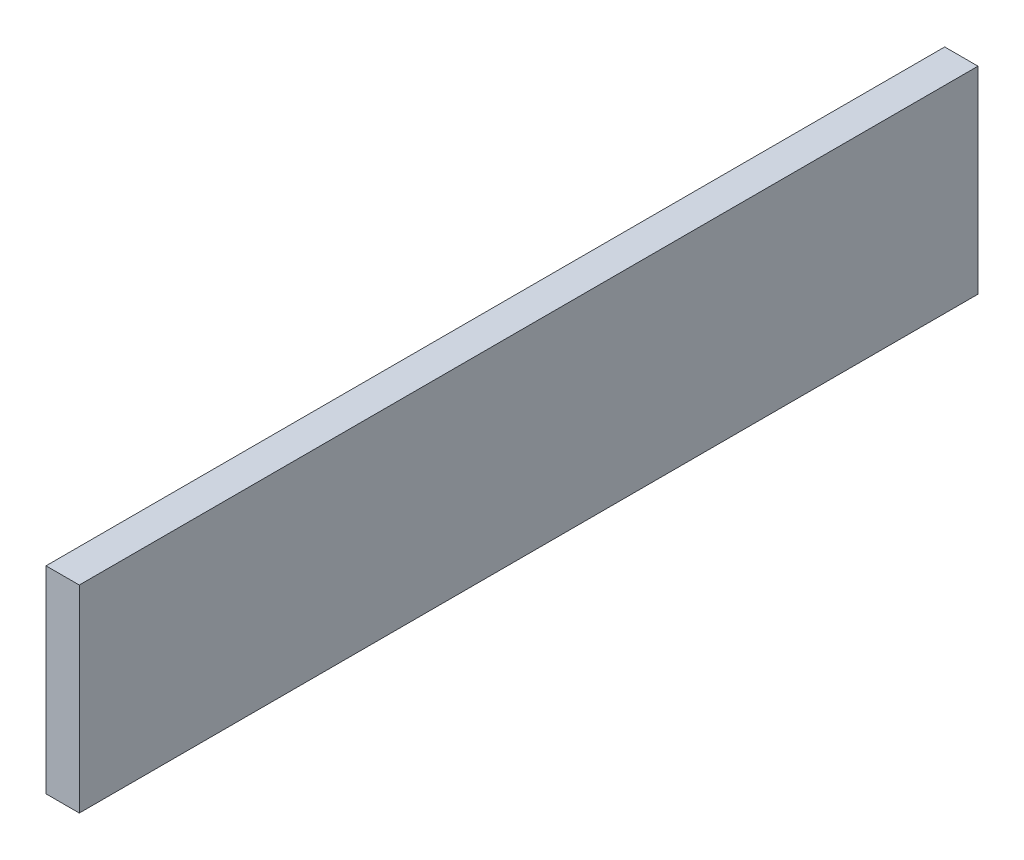
SolidWorks part; units mm, degrees
ref_plane "Alzado" through (0, 0, 0) normal (0, 0, 1) x (1, 0, 0)
ref_plane "Planta" through (0, 0, 0) normal (0, 1, 0) x (1, 0, 0)
ref_plane "Vista lateral" through (0, 0, 0) normal (1, 0, 0) x (0, 0, -1)
sketch "Croquis1" plane through (0, 0, 0) normal (1, 0, 0) x (0, 0, -1)
  line L1 (0, 0) -> (405, 0)
  line L2 (0, 0) -> (0, 89)
  line L3 (0, 89) -> (405, 89)
  line L4 (405, 0) -> (405, 89)
  dimension "D1" = 89
  dimension "D2" = 405
extrude "Saliente-Extruir1" add sketch "Croquis1" along normal blind 15
sketch "Croquis2" plane through (15, 0, 0) normal (1, 0, 0) x (0, 0, -1)
  line L0 (202.5, 0) -> (202.5, 89) construction
  line L1 (0, 0) -> (405, 0) construction
  line L2 (405, 89) -> (0, 89) construction
  line L3 (0, 44.5) -> (405, 44.5) construction
  line L4 (0, 89) -> (0, 0) construction
  line L5 (405, 0) -> (405, 89) construction
